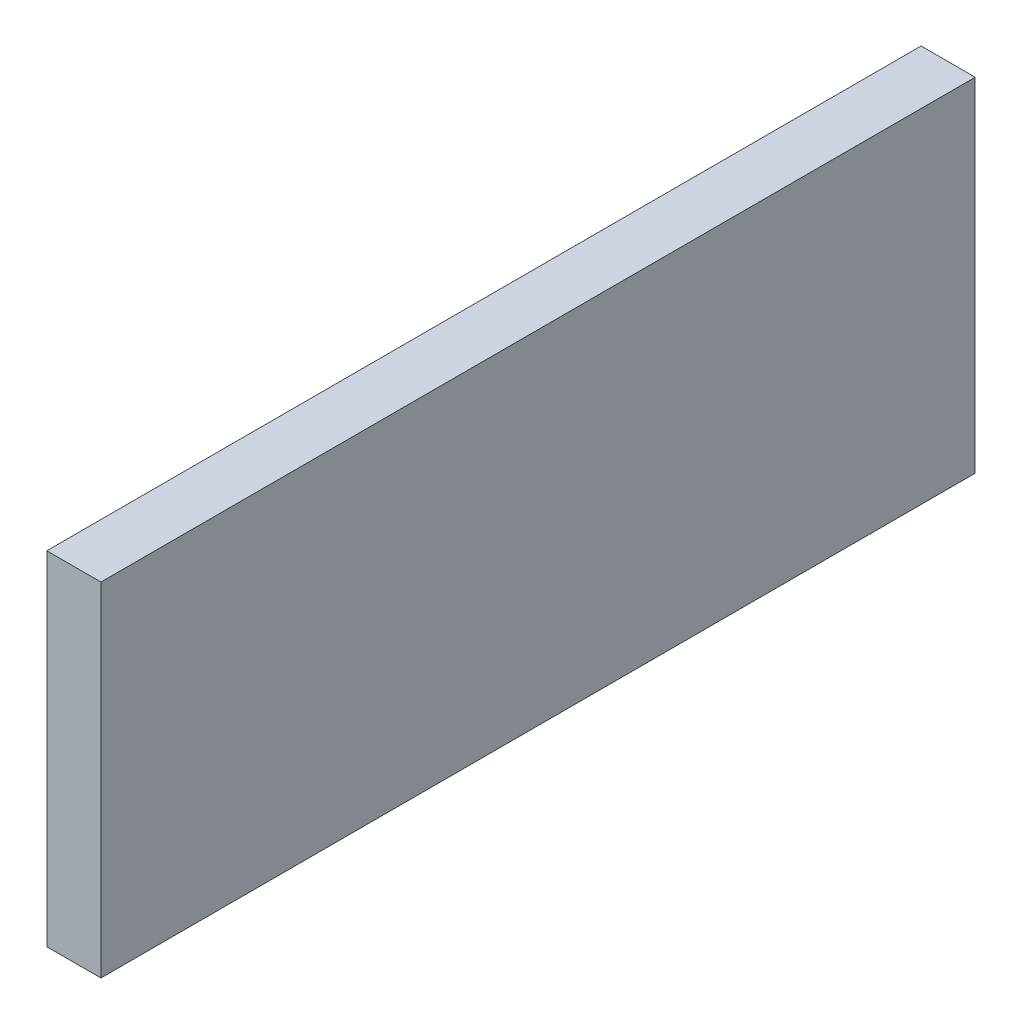
SolidWorks part; units mm, degrees
ref_plane "Front Plane" through (0, 0, 0) normal (0, 0, 1) x (1, 0, 0)
ref_plane "Top Plane" through (0, 0, 0) normal (0, 1, 0) x (1, 0, 0)
ref_plane "Right Plane" through (0, 0, 0) normal (1, 0, 0) x (0, 0, -1)
sketch "Sketch1" plane through (-1199.0067, 0, 0) normal (-1, 0, 0) x (0, 0, 1)
  line L8 (581.1657, 28.7635) -> (1196.3622, 28.7635)
  line L9 (1196.3622, 28.7635) -> (1196.3622, 270.0635)
  line L10 (1196.3622, 270.0635) -> (581.1657, 270.0635)
  line L11 (581.1657, 270.0635) -> (581.1657, 28.7635)
  line L12 (581.1657, 28.7635) -> (1196.3622, 28.7635)
  line L13 (1196.3622, 28.7635) -> (1196.3622, 270.0635)
  line L14 (1196.3622, 270.0635) -> (581.1657, 270.0635)
  line L15 (581.1657, 270.0635) -> (581.1657, 28.7635)
  dimension "D1" = 19.05
extrude "Boss-Extrude1" add sketch "Sketch1" against normal up to vertex (38.1 mm away)
